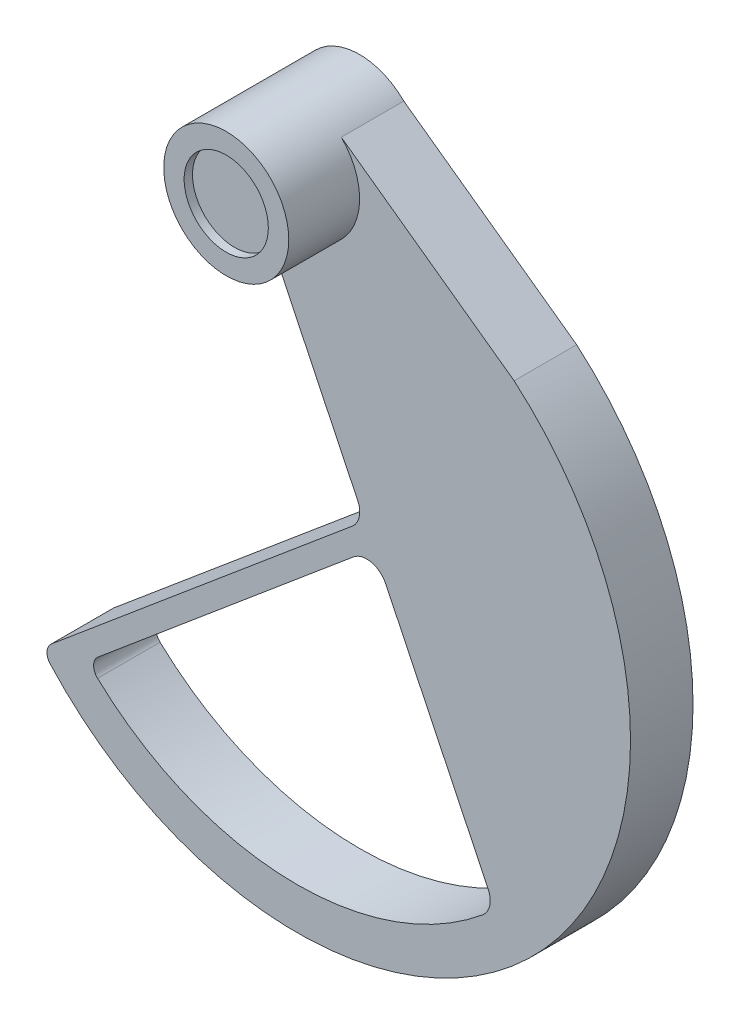
SolidWorks part; units mm, degrees
ref_plane "正面" through (0, 0, 0) normal (0, 0, 1) x (1, 0, 0)
ref_plane "平面" through (0, 0, 0) normal (0, 1, 0) x (1, 0, 0)
ref_plane "右側面" through (0, 0, 0) normal (1, 0, 0) x (0, 0, -1)
sketch "ｽｹｯﾁ4" plane through (0, 0, 0) normal (0, 0, 1) x (1, 0, 0)
  line L0 (0, 0.7897) -> (0, 0)
  line L1 (-53.6231, -124.9951) -> (-58.9406, -129.4571)
  line L3 (-10.6066, -10.6066) -> (14.5363, -62.8896)
  line L4 (-53.6231, -124.9951) -> (13.2442, -68.8868)
  line L5 (21.2324, -76.8138) -> (45.8448, -127.9938)
  line L6 (10.6066, 10.6066) -> (52.0762, -19.2705)
  line L7 (-58.0696, -135.2532) -> (-57.9498, -135.1527)
  line L8 (-47.7477, -126.5866) -> (13.5112, -75.1515)
  arc A1 (-59.2335, -133.7716) -> (52.0762, -19.2705) centre (0, -80) ccw
  arc A2 (-47.8702, -131.073) -> (44.5187, -134.0193) centre (0, -80) ccw
  arc A3 (10.6066, 10.6066) -> (-10.6066, -10.6066) centre (0, 0) ccw
  arc A4 (-59.2335, -133.7716) -> (-58.9406, -129.4571) centre (-57.0123, -131.7552) cw
  arc A5 (-47.8702, -131.073) -> (-47.7477, -126.5866) centre (-45.8186, -128.8841) cw
  arc A6 (13.5112, -75.1515) -> (21.2324, -76.8138) centre (16.7264, -78.9807) cw
  arc A7 (13.2442, -68.8868) -> (14.5363, -62.8896) centre (10.0302, -65.0566) ccw
  arc A8 (45.8448, -127.9938) -> (44.5187, -134.0193) centre (41.3388, -130.1608) cw
  point P18 (-61.2836, -131.423)
  point P21 (-50.2744, -128.7081)
  point P24 (18.4421, -71.0114)
  dimension "D3" = 140
  dimension "D4" = 30
  dimension "D5" = 5
  dimension "D6" = 3
  dimension "D7" = 3
  dimension "D8" = 5
  dimension "D9" = 5
  dimension "D10" = 5
  dimension "D2" = 5
extrude "ﾎﾞｽ - 押し出し1" add sketch "ｽｹｯﾁ4" along normal blind 15
sketch "ｽｹｯﾁ5" plane through (0, 0, 15) normal (0, 0, 1) x (1, 0, 0)
  circle A0 centre (0, 0) radius 15
  dimension "D1" = 30
extrude "ﾎﾞｽ - 押し出し2" add sketch "ｽｹｯﾁ5" along normal blind 17
sketch "ｽｹｯﾁ7" plane through (0, 0, 32) normal (0, 0, 1) x (1, 0, 0)
  circle A0 centre (0, 0) radius 10.1
  dimension "D1" = 20.2
extrude "ｶｯﾄ - 押し出し1" cut sketch "ｽｹｯﾁ7" against normal blind 2
